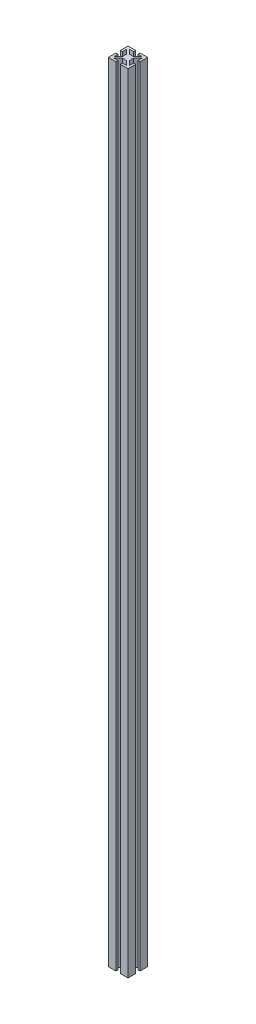
SolidWorks part; units mm, degrees
ref_plane "Front Plane" through (0, 0, 0) normal (0, 0, 1) x (1, 0, 0)
ref_plane "Top Plane" through (0, 0, 0) normal (0, 1, 0) x (1, 0, 0)
ref_plane "Right Plane" through (0, 0, 0) normal (1, 0, 0) x (0, 0, -1)
sketch "Sketch2" plane through (0.5947, 0, 0.5947) normal (0, 1, 0) x (1, 0, 0)
  line L0 (-0.5947, 0.5947) -> (-0.5947, 20.2394) construction
  line L1 (-0.5947, 0.5947) -> (-20.2394, 0.5947) construction
  line L2 (-0.5947, 0.5947) -> (-20.2394, 20.2394) construction
  line L3 (-19.6447, 19.6447) -> (-4.6587, 19.6447)
  line L4 (-4.6587, 19.6447) -> (-4.6587, 15.5807)
  line L5 (-4.6587, 15.5807) -> (-12.707, 15.5807)
  line L6 (-12.707, 15.5807) -> (-4.4774, 7.3511)
  line L7 (-4.4774, 7.3511) -> (3.288, 7.3511)
  line L8 (-19.6447, 19.6447) -> (-19.6447, 4.6587)
  line L9 (-19.6447, 4.6587) -> (-15.5807, 4.6587)
  line L10 (-15.5807, 4.6587) -> (-15.5807, 12.707)
  line L11 (-15.5807, 12.707) -> (-7.3511, 4.4774)
  line L12 (-7.3511, 4.4774) -> (-7.3511, -3.288)
  line L13 (-4.4774, -6.1617) -> (3.288, -6.1617)
  line L14 (-12.707, -14.3913) -> (-4.4774, -6.1617)
  line L15 (-4.6587, -14.3913) -> (-12.707, -14.3913)
  line L16 (-4.6587, -18.4553) -> (-4.6587, -14.3913)
  line L17 (-19.6447, -18.4553) -> (-4.6587, -18.4553)
  line L18 (-19.6447, -18.4553) -> (-19.6447, -3.4693)
  line L19 (-19.6447, -3.4693) -> (-15.5807, -3.4693)
  line L20 (-15.5807, -3.4693) -> (-15.5807, -11.5176)
  line L21 (-15.5807, -11.5176) -> (-7.3511, -3.288)
  line L22 (11.5176, 15.5807) -> (3.288, 7.3511)
  line L23 (3.4693, 15.5807) -> (11.5176, 15.5807)
  line L24 (3.4693, 19.6447) -> (3.4693, 15.5807)
  line L25 (18.4553, 19.6447) -> (3.4693, 19.6447)
  line L26 (18.4553, 19.6447) -> (18.4553, 4.6587)
  line L27 (18.4553, 4.6587) -> (14.3913, 4.6587)
  line L28 (14.3913, 4.6587) -> (14.3913, 12.707)
  line L29 (14.3913, 12.707) -> (6.1617, 4.4774)
  line L30 (6.1617, 4.4774) -> (6.1617, -3.288)
  line L31 (14.3913, -11.5176) -> (6.1617, -3.288)
  line L32 (14.3913, -3.4693) -> (14.3913, -11.5176)
  line L33 (18.4553, -3.4693) -> (14.3913, -3.4693)
  line L34 (18.4553, -18.4553) -> (18.4553, -3.4693)
  line L35 (18.4553, -18.4553) -> (3.4693, -18.4553)
  line L36 (3.4693, -18.4553) -> (3.4693, -14.3913)
  line L37 (3.4693, -14.3913) -> (11.5176, -14.3913)
  line L38 (11.5176, -14.3913) -> (3.288, -6.1617)
  point P26 (-7.3511, 0.5947)
  point P27 (-0.5947, 7.3511)
  point P44 (-0.5947, -6.1617)
  dimension "D1" = 38.1
  dimension "D2" = 8.128
  dimension "D3" = 13.5128
  dimension "D4" = 4.064
  dimension "D5" = 4.064
extrude "Boss-Extrude1" add sketch "Sketch2" along normal blind 1524
other "1515<1>"
